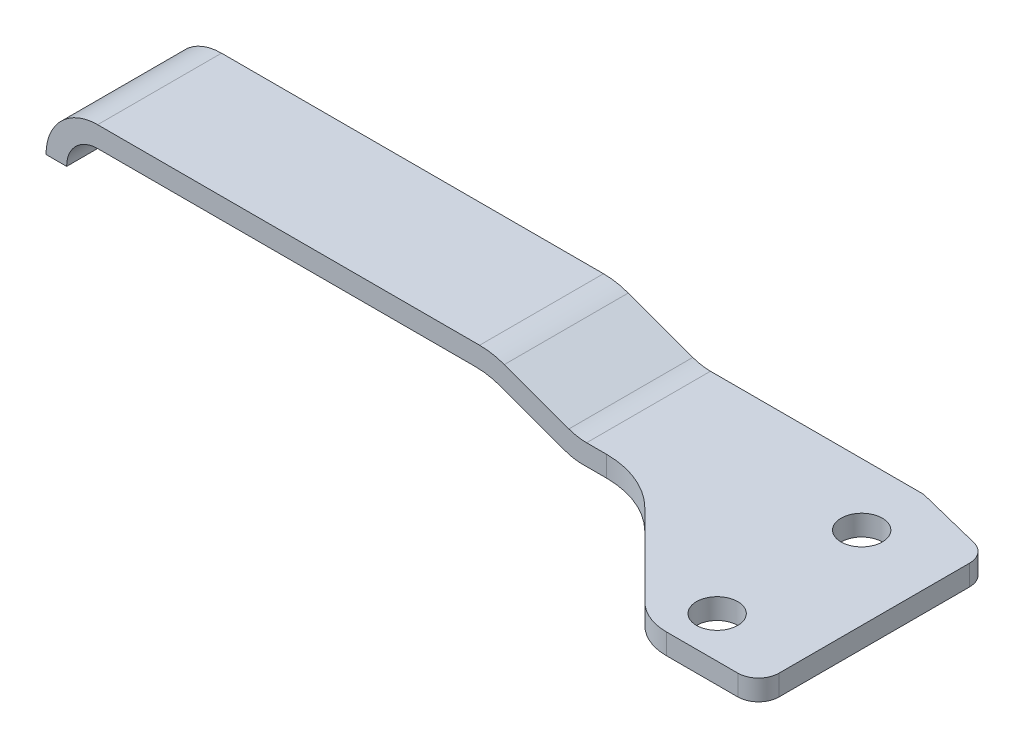
SolidWorks part; units mm, degrees
ref_plane "Front Plane" through (0, 0, 0) normal (0, 0, 1) x (1, 0, 0)
ref_plane "Top Plane" through (0, 0, 0) normal (0, 1, 0) x (1, 0, 0)
ref_plane "Right Plane" through (0, 0, 0) normal (1, 0, 0) x (0, 0, -1)
sketch "Sketch2" plane through (0, 0, 0) normal (0, 1, 0) x (1, 0, 0)
  line L1 (-64.3001, 19.05) -> (64.3001, 19.05)
  line L2 (-64.3001, 19.05) -> (-64.3001, -19.05)
  line L3 (-64.3001, -19.05) -> (64.3001, -19.05)
  line L4 (64.3001, 19.05) -> (64.3001, -19.05)
  line L5 (-64.3001, 19.05) -> (64.3001, -19.05) construction
  line L6 (-64.3001, -19.05) -> (64.3001, 19.05) construction
  point P0 (0, 0)
  dimension "D1" = 38.1
  dimension "D2" = 128.6002
extrude "Boss-Extrude1" add sketch "Sketch2" along normal blind 7.9375
sketch "Sketch4" plane through (0, 7.9375, 0) normal (0, 1, 0) x (1, 0, 0)
  line L0 (64.3001, 19.05) -> (51.6001, 19.05)
  line L1 (64.3001, 19.05) -> (-64.3001, 19.05) construction
  line L2 (51.6001, 19.05) -> (64.3001, 15.8835)
  line L3 (64.3001, -19.05) -> (64.3001, 19.05) construction
  line L4 (64.3001, 15.8835) -> (64.3001, 19.05)
  dimension "D1" = 115.9002
  dimension "D2" = 14
extrude "Cut-Extrude1" cut sketch "Sketch4" against normal blind 7.9375
sketch "Sketch5" plane through (0, 7.9375, 0) normal (0, 1, 0) x (1, 0, 0)
  line L0 (-64.3001, 0) -> (21.8605, 0)
  line L1 (-64.3001, 19.05) -> (-64.3001, -19.05) construction
  line L3 (-64.3001, -19.05) -> (64.3001, -19.05) construction
  line L4 (50.1269, -19.05) -> (-64.3001, -19.05)
  line L5 (-64.3001, -19.05) -> (-64.3001, 0)
  line L7 (31.9723, -4.1884) -> (44.5053, -16.7214)
  line L9 (64.3001, -19.05) -> (64.3001, 15.8835) construction
  arc A0 (44.5053, -16.7214) -> (50.1269, -19.05) centre (50.1269, -11.0998) ccw
  arc A1 (31.9723, -4.1884) -> (21.8605, 0) centre (21.8605, -14.3002) ccw
  dimension "D3" = 15.9004
  dimension "D4" = 28.6004
  dimension "D1" = 14.1732
  dimension "D2" = 45
extrude "Cut-Extrude3" cut sketch "Sketch5" against normal blind 7.9375
fillet "Fillet3" radius 3.175 3 edges at (51.6001, 3.9688, -19.05) (64.3001, 3.9688, 19.05) (64.3001, 3.9688, -15.8835)
sketch "Sketch6" plane through (0, 7.9375, 0) normal (0, 1, 0) x (1, 0, 0)
  line L0 (51.2103, 19.05) -> (-64.3001, 19.05) construction
  line L1 (-64.3001, 19.05) -> (-64.3001, 0) construction
  line L3 (51.6001, 9.525) -> (51.6001, -54.4914) construction
  circle A0 centre (51.6001, 9.525) radius 3.175
  circle A1 centre (51.6001, -12.7) radius 3.175
  dimension "D2" = 6.35
  dimension "D4" = 6.35
  dimension "D1" = 9.525
  dimension "D3" = 115.9002
  dimension "D5" = 22.225
extrude "Cut-Extrude4" cut sketch "Sketch6" against normal blind 7.9375
sketch "Sketch12" plane through (0, 0, -19.05) normal (0, 0, -1) x (-1, 0, 0)
  line L0 (64.3001, 7.9375) -> (64.3001, 0) construction
  line L1 (59.8139, 4.7625) -> (-1.7666, 4.7625)
  line L2 (-51.2103, 7.9375) -> (64.3001, 7.9375) construction
  line L3 (64.3001, 0) -> (-17.8007, 0)
  line L4 (61.1251, -3.6777) -> (61.1251, 2.5923) construction
  line L5 (-6.1799, 7.2666) -> (-16.1041, 3.6545)
  line L6 (-18.8233, 3.175) -> (-64.3001, 3.175)
  line L7 (-64.3001, 0) -> (-64.3001, 7.9375) construction
  line L8 (64.3001, 0) -> (64.3001, 7.9375)
  line L9 (64.3001, 7.9375) -> (56.3626, 7.9375)
  line L10 (-51.2103, 0) -> (64.3001, 0) construction
  line L11 (-64.3001, 3.175) -> (-64.3001, 7.9375)
  line L12 (-64.3001, 7.9375) -> (-2.3749, 7.9375)
  line L13 (-5.5717, 4.0916) -> (-15.5308, 0.4668)
  arc A0 (-2.3749, 7.9375) -> (-12.4172, 1.6) centre (-2.3749, -3.1877) ccw
  arc A1 (-24.6158, 3.175) -> (-10.6377, 5.6441) centre (-18.2499, 7.9375) ccw
  arc A2 (-18.8233, 3.175) -> (-16.1041, 3.6545) centre (-18.8233, 11.1252) ccw
  arc A4 (-1.7666, 4.7625) -> (-5.5717, 4.0916) centre (-1.7666, -6.3627) ccw
  arc A5 (48.4251, 0) -> (56.3626, 7.9375) centre (56.3626, 0) ccw
  arc A6 (51.6001, 0) -> (56.3626, 4.7625) centre (56.3626, 0) ccw
  line M3 (64.3001, 7.9375) -> (-51.2103, 7.9375)
  line M4 (-51.2103, 7.9375) -> (-51.2103, 0)
  line M5 (-51.2103, 0) -> (64.3001, 0)
  line M6 (64.3001, 0) -> (64.3001, 7.9375)
  dimension "D1" = 22.2504
  dimension "D2" = 15.9004
  dimension "D8" = 11.1252
  dimension "D9" = 15.875
  dimension "D3" = 66.675
  dimension "D4" = 4.7625
  dimension "D5" = 82.55
  dimension "D6" = 20
  dimension "D7" = 3.175
  dimension "D10" = 3.175
extrude "Cut-Extrude8" cut sketch "Sketch12" against normal through all and the other way through all contours L6 A2 L5 A0 M3 M4 | L12 L11 L6 M4 | A5 M6 M3 | A6 L1 A4 L13 A1 L3 M5
